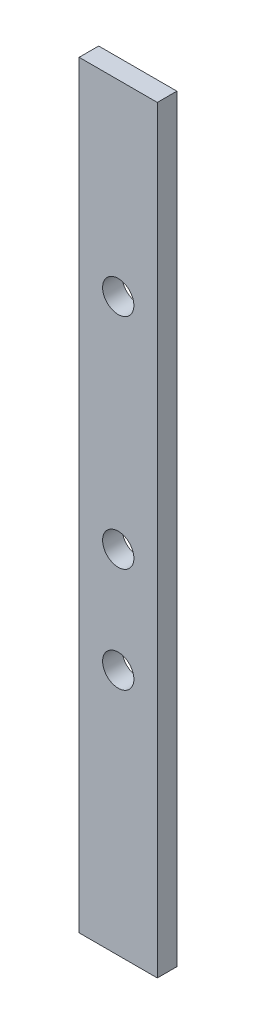
SolidWorks part; units mm, degrees
ref_plane "Front Plane" through (0, 0, 0) normal (0, 0, 1) x (1, 0, 0)
ref_plane "Top Plane" through (0, 0, 0) normal (0, 1, 0) x (1, 0, 0)
ref_plane "Right Plane" through (0, 0, 0) normal (1, 0, 0) x (0, 0, -1)
sketch "Sketch2" plane through (0, 0, 0) normal (0, 1, 0) x (1, 0, 0)
  line L0 (0, 0) -> (12.7, 0)
  line L1 (0, 0) -> (0, 3.175)
  line L2 (12.7, 0) -> (12.7, 3.175)
  line L3 (0, 3.175) -> (12.7, 3.175)
extrude "Boss-Extrude1" add sketch "Sketch2" along normal blind 123.19
sketch "Sketch3" plane through (0, 0, 0) normal (0, 0, 1) x (1, 0, 0)
  line L0 (6.35, 123.19) -> (6.35, 92.71) construction
  line L1 (0, 123.19) -> (12.7, 123.19) construction
  line L2 (6.35, 0) -> (6.35, 57.15) construction
  line L3 (0, 0) -> (12.7, 0) construction
  line L4 (6.35, 0) -> (6.35, 25.4) construction
  line L5 (6.35, 0) -> (6.35, 40.132) construction
  circle A0 centre (6.35, 92.71) radius 2.54
  circle A1 centre (6.35, 57.15) radius 2.54
  circle A2 centre (6.35, 40.132) radius 2.54
extrude "Cut-Extrude1" cut sketch "Sketch3" against normal blind 25.4
